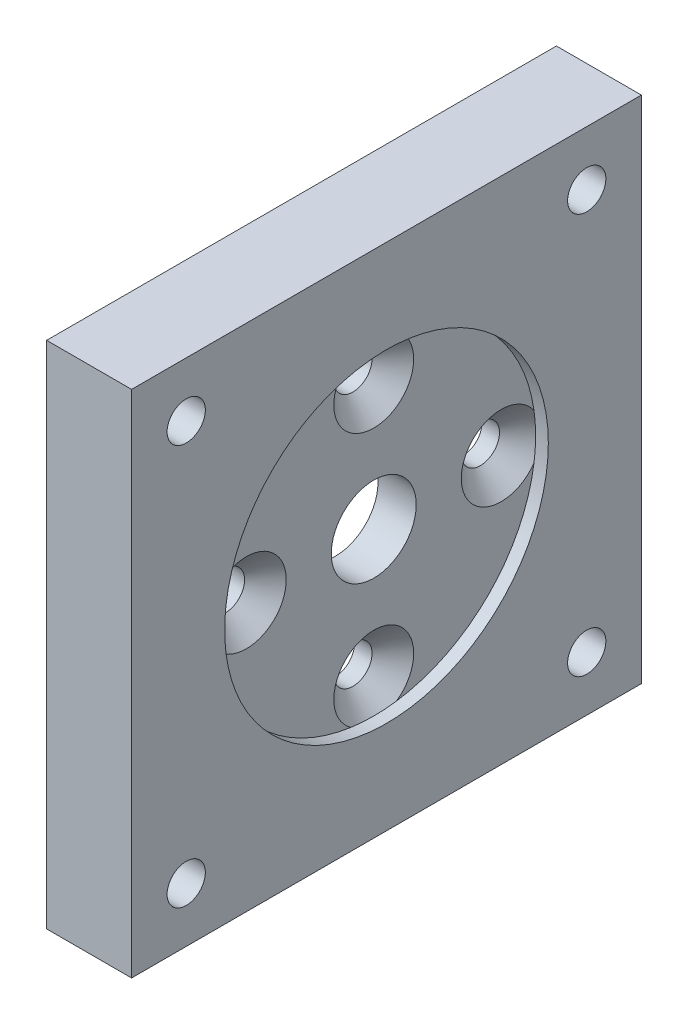
SolidWorks part; units mm, degrees
material "1060 Alloy"
ref_plane "Front Plane" through (0, 0, 0) normal (0, 0, 1) x (1, 0, 0)
ref_plane "Top Plane" through (0, 0, 0) normal (0, 1, 0) x (1, 0, 0)
ref_plane "Right Plane" through (0, 0, 0) normal (1, 0, 0) x (0, 0, -1)
sketch "Sketch1" plane through (0, 0, 0) normal (1, 0, 0) x (0, 0, -1)
  line L1 (-30, 30) -> (30, 30)
  line L2 (-30, 30) -> (-30, -30)
  line L3 (-30, -30) -> (30, -30)
  line L4 (30, 30) -> (30, -30)
  line L5 (-30, 30) -> (30, -30) construction
  line L6 (-30, -30) -> (30, 30) construction
  point P0 (0, 0)
  dimension "D1" = 60
extrude "Extrude1" add sketch "Sketch1" along normal blind 10
sketch "Sketch3" plane through (10, 0, 0) normal (1, 0, 0) x (0, 0, -1)
  circle A0 centre (0, 0) radius 5
  dimension "D1" = 10
extrude "Extrude2" cut sketch "Sketch3" against normal through all
sketch "Sketch5" plane through (10, 0, 0) normal (1, 0, 0) x (0, 0, -1)
  circle A0 centre (0, 0) radius 19.05
  dimension "D1" = 38.1
extrude "Extrude3" cut sketch "Sketch5" against normal blind 1.5
sketch "Sketch6" plane through (0, 0, 0) normal (-1, 0, 0) x (0, 0, 1)
  circle A0 centre (0, 0) radius 22.4
  dimension "D1" = 44.8
extrude "Extrude4" cut sketch "Sketch6" against normal blind 4
sketch "Sketch7" plane through (0, 0, 0) normal (-1, 0, 0) x (0, 0, 1)
  line L1 (-23.57, -23.57) -> (23.57, -23.57)
  line L2 (-23.57, -23.57) -> (-23.57, 23.57)
  line L3 (-23.57, 23.57) -> (23.57, 23.57)
  line L4 (23.57, -23.57) -> (23.57, 23.57)
  line L5 (-23.57, -23.57) -> (23.57, 23.57) construction
  line L6 (-23.57, 23.57) -> (23.57, -23.57) construction
  circle A0 centre (23.57, 23.57) radius 2.25
  circle A1 centre (-23.57, 23.57) radius 2.25
  circle A2 centre (23.57, -23.57) radius 2.25
  circle A3 centre (-23.57, -23.57) radius 2.25
  point P0 (0, 0)
  dimension "D3" = 4.5
  dimension "D4" = 4.5
  dimension "D5" = 4.5
  dimension "D6" = 4.5
  dimension "D1" = 47.14
  dimension "D2" = 47.14
extrude "Extrude6" cut sketch "Sketch7" against normal through all contours A1 | A3 | A2 | A0
sketch "Sketch8" plane through (8.5, 0, 0) normal (1, 0, 0) x (0, 0, -1)
  circle A0 centre (0, 0) radius 15
  circle A2 centre (0, 15) radius 2.25
  circle A3 centre (-15, 0) radius 2.25
  circle A4 centre (0, -15) radius 2.25
  circle A5 centre (15, 0) radius 2.25
  dimension "D1" = 30
  dimension "D2" = 4.5
  dimension "D3" = 4.5
  dimension "D4" = 4.5
  dimension "D5" = 4.5
extrude "Extrude7" cut sketch "Sketch8" against normal through all contours A5 | A4 | A3 | A2
hole_wizard "CSK for M4 Flat Head Machine Screw1" positions "3DSketch1" profile "Sketch9" countersink size "M4" standard "Ansi Metric"
sketch3d "3DSketch1"
  line L0 (4, 15, 0) -> (8.5, 15, 0) construction
  line L1 (4, 0, 15) -> (8.5, 0, 15) construction
  line L2 (4, -15, 0) -> (8.5, -15, 0) construction
  line L3 (4, 0, -15) -> (8.5, 0, -15) construction
  point P0 (8.5, 15, 0)
  point P4 (8.5, 0, 15)
  point P8 (8.5, -15, 0)
  point P12 (8.5, 0, -15)
sketch "Sketch9" plane through (8.5, 15, 0) normal (0, 1, 0) x (0, 0, -1)
  line L0 (0, 0) -> (0, 8.5)
  line L1 (0, 8.5) -> (2.25, 8.5)
  line L2 (2.25, 8.5) -> (2.25, 2.45)
  line L3 (2.25, 2.45) -> (4.7, 0)
  line L5 (4.7, 0) -> (0, 0)
  line L6 (-2.25, 2.45) -> (-4.7, 0) construction
  line L11 (0, -6.35) -> (0, 107.95) construction
  dimension "Thru Hole Dia." = 4.5
  dimension "Thru Hole Depth" = 8.5
  dimension "Near C'Sink Dia." = 9.4
  dimension "Near C'Sink Angle" = 90
